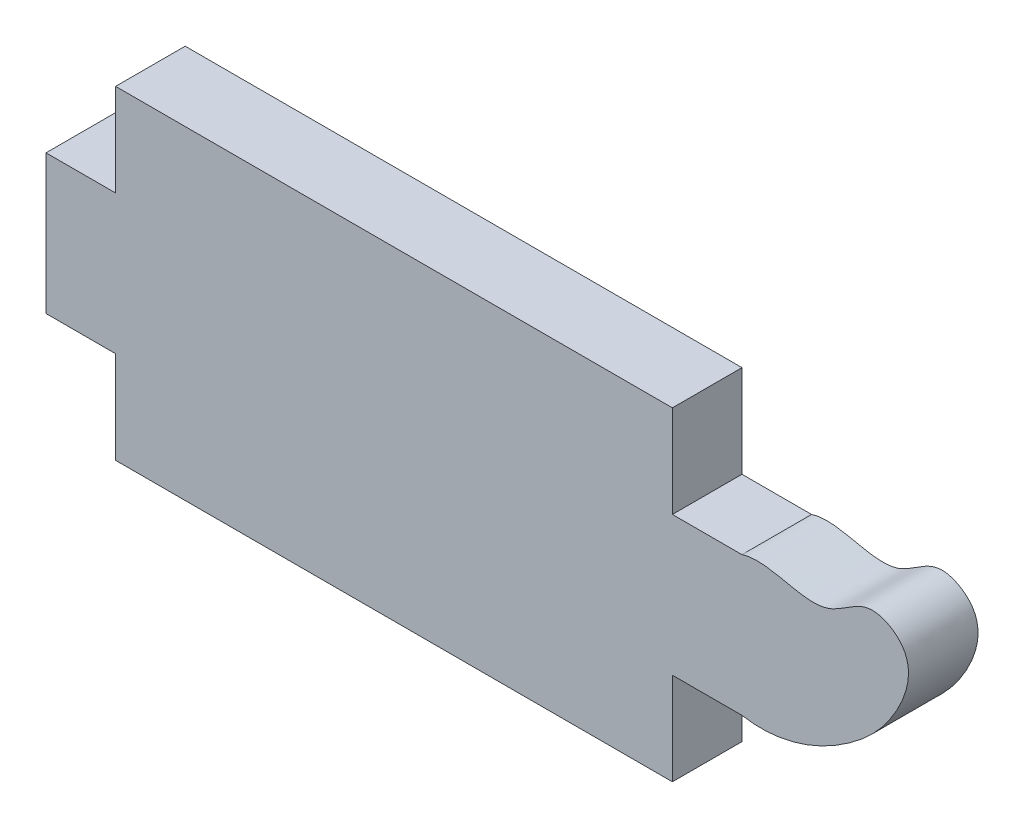
SolidWorks part; units mm, degrees
ref_plane "Front Plane" through (0, 0, 0) normal (0, 0, 1) x (1, 0, 0)
ref_plane "Top Plane" through (0, 0, 0) normal (0, 1, 0) x (1, 0, 0)
ref_plane "Right Plane" through (0, 0, 0) normal (1, 0, 0) x (0, 0, -1)
sketch "Sketch1" plane through (0, 0, 0) normal (0, 0, 1) x (1, 0, 0)
  line L0 (-25.4, 33.2376) -> (-25.4, 37.4504) construction
  line L1 (0, 33.2376) -> (-25.4, 33.2376)
  line L3 (0, 48.0131) -> (-25.4, 48.0131)
  line L4 (-28.575, 37.4504) -> (-28.575, 43.8004)
  line L7 (-28.575, 43.8004) -> (-25.4, 43.8004)
  line L8 (-25.4, 48.0131) -> (-25.4, 43.8004)
  line L9 (0, 33.2376) -> (0, 37.4504) construction
  line L12 (-28.575, 37.4504) -> (-25.4, 37.4504)
  line L13 (-25.4, 33.2376) -> (-25.4, 37.4504)
  line L16 (3.175, 43.8004) -> (0, 43.8004)
  line L17 (0, 48.0131) -> (0, 43.8004)
  line L21 (3.175, 37.4504) -> (0, 37.4504)
  line L22 (0, 33.2376) -> (0, 37.4504)
  spline S0 degree 3 poles (3.175, 37.4504) (5.0221, 37.1185) (7.7515, 38.2603) (10.2328, 40.7568) (11.32, 43.6261) (8.8237, 45.0464) (6.7279, 42.6784) (4.4316, 44.2179) (3.175, 43.8004) knots 0 0 0 0 0.293581 0.427452 0.586796 0.673694 0.788354 1 1 1 1
  dimension "D1" = 6.35
  dimension "D2" = 6.35
extrude "Boss-Extrude1" add sketch "Sketch1" against normal blind 3.175 contours L3 L8 L7 L4 L12 L13 L1 L22 L21 S0 L16 L17
